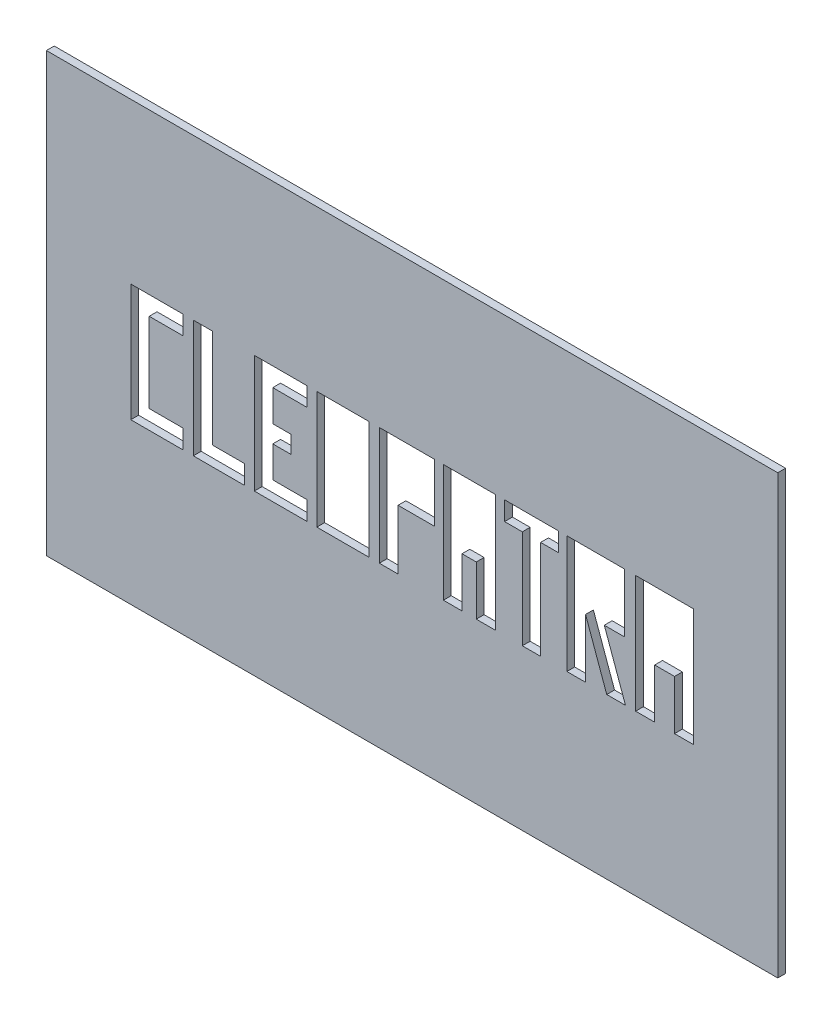
SolidWorks part; units mm, degrees
ref_plane "Front Plane" through (0, 0, 0) normal (0, 0, 1) x (1, 0, 0)
ref_plane "Top Plane" through (0, 0, 0) normal (0, 1, 0) x (1, 0, 0)
ref_plane "Right Plane" through (0, 0, 0) normal (1, 0, 0) x (0, 0, -1)
sketch "Sketch1" plane through (0, 0, 0) normal (0, 0, 1) x (1, 0, 0)
  line L1 (-148.59, 88.9) -> (148.59, 88.9)
  line L2 (-148.59, 88.9) -> (-148.59, -88.9)
  line L3 (-148.59, -88.9) -> (148.59, -88.9)
  line L4 (148.59, 88.9) -> (148.59, -88.9)
  line L5 (-148.59, 88.9) -> (148.59, -88.9) construction
  line L6 (-148.59, -88.9) -> (148.59, 88.9) construction
  point P1 (0, 0)
  dimension "D1" = 297.18
  dimension "D2" = 177.8
extrude "Boss-Extrude1" add sketch "Sketch1" along normal blind 3.175
ref_plane "Plane1" through (0, 0, 3.175) normal (0, 0, 1) x (1, 0, 0)
sketch "Sketch3" plane through (0, 0, 3.175) normal (0, 0, 1) x (1, 0, 0)
  line L0 (-114.3, 0) -> (114.3, 0)
  line L1 (-114.3, 23.886) -> (114.3, 23.886)
  line L2 (-114.3, 23.886) -> (-114.3, -23.886)
  line L3 (-114.3, -23.886) -> (114.3, -23.886)
  line L4 (114.3, 23.886) -> (114.3, -23.886)
  line L5 (-114.3, 23.886) -> (114.3, -23.886) construction
  line L6 (-114.3, -23.886) -> (114.3, 23.886) construction
  line L7 (114.3, 0) -> (114.3, 23.886)
  line L8 (-114.3, 23.886) -> (-88.9, 23.886) construction
  line L9 (-88.9, 23.886) -> (-88.9, -23.886) construction
  line L10 (-88.9, -23.886) -> (-64.111, -23.886) construction
  line L11 (-64.111, -23.886) -> (-64.111, 23.886) construction
  line L12 (-64.111, 23.886) -> (-38.711, 23.886) construction
  line L13 (-38.711, 23.886) -> (-38.711, -23.886) construction
  line L14 (-38.711, -23.886) -> (-13.311, -23.886) construction
  line L15 (-38.711, -23.886) -> (-13.311, -23.886) construction
  line L16 (-13.311, -23.886) -> (-13.311, 23.886) construction
  line L17 (-13.311, 23.886) -> (12.7173, 23.886) construction
  line L18 (12.7173, 23.886) -> (12.7173, -23.886) construction
  line L19 (12.7173, -23.886) -> (37.5864, -23.886) construction
  line L20 (37.5864, -23.886) -> (37.5864, 23.886) construction
  line L21 (37.5864, 23.886) -> (62.8944, 23.886) construction
  line L22 (62.8944, 23.886) -> (62.8944, -23.886) construction
  line L23 (62.8944, -23.886) -> (90.8355, -23.886) construction
  line L24 (90.8355, -23.886) -> (90.8355, 23.886) construction
  line L25 (70.4868, 0) -> (78.1068, 0)
  line L26 (-114.3, 23.886) -> (-106.8152, 23.886)
  line L27 (-114.3, 23.886) -> (-114.3, -23.886)
  line L28 (-114.3, -23.886) -> (-106.8152, -23.886)
  line L29 (-106.8152, 23.886) -> (-106.8152, -23.886)
  line L30 (-88.9, 23.886) -> (-81.1854, 23.886)
  line L31 (-88.9, 23.886) -> (-88.9, -23.886)
  line L32 (-88.9, -23.886) -> (-81.1854, -23.886)
  line L33 (-81.1854, 23.886) -> (-81.1854, -23.886)
  line L34 (-64.111, 23.886) -> (-56.6089, 23.886)
  line L35 (-64.111, 23.886) -> (-64.111, -23.886)
  line L36 (-64.111, -23.886) -> (-56.6089, -23.886)
  line L37 (-56.6089, 23.886) -> (-56.6089, -23.886)
  line L38 (-64.111, -23.886) -> (-42.7407, -23.886)
  line L39 (-64.111, -23.886) -> (-64.111, -16.2136)
  line L40 (-64.111, -16.2136) -> (-42.7407, -16.2136)
  line L41 (-42.7407, -23.886) -> (-42.7407, -16.2136)
  line L42 (-64.111, 23.886) -> (-42.7407, 23.886)
  line L43 (-64.111, 23.886) -> (-64.111, 16.2625)
  line L44 (-64.111, 16.2625) -> (-42.7407, 16.2625)
  line L45 (-42.7407, 23.886) -> (-42.7407, 16.2625)
  line L46 (-64.1233, 3.5401) -> (-49.2238, 3.5401)
  line L47 (-64.1233, 3.5401) -> (-64.1233, -3.5401)
  line L48 (-64.1233, -3.5401) -> (-49.2238, -3.5401)
  line L49 (-49.2238, 3.5401) -> (-49.2238, -3.5401)
  line L50 (-64.1233, 3.5401) -> (-49.2238, -3.5401) construction
  line L51 (-64.1233, -3.5401) -> (-49.2238, 3.5401) construction
  line L52 (-88.9, -23.886) -> (-68.0194, -23.886)
  line L53 (-88.9, -23.886) -> (-88.9, -16.2136)
  line L54 (-88.9, -16.2136) -> (-68.0194, -16.2136)
  line L55 (-68.0194, -23.886) -> (-68.0194, -16.2136)
  line L56 (-38.711, 23.886) -> (-17.462, 23.886)
  line L57 (-38.711, 23.886) -> (-38.711, -23.886)
  line L58 (-38.711, -23.886) -> (-17.462, -23.886)
  line L59 (-17.462, 23.886) -> (-17.462, -23.886)
  line L60 (-31.1625, 16.2136) -> (-25.0105, 16.2136)
  line L61 (-31.1625, 16.2136) -> (-31.1625, -16.2136)
  line L62 (-31.1625, -16.2136) -> (-25.0105, -16.2136)
  line L63 (-25.0105, 16.2136) -> (-25.0105, -16.2136)
  line L64 (-31.1625, 16.2136) -> (-25.0105, -16.2136) construction
  line L65 (-31.1625, -16.2136) -> (-25.0105, 16.2136) construction
  line L66 (-114.3, 23.886) -> (-93.1225, 23.886)
  line L67 (-114.3, 23.886) -> (-114.3, 16.2625)
  line L68 (-114.3, 16.2625) -> (-93.1225, 16.2625)
  line L69 (-93.1225, 23.886) -> (-93.1225, 16.2625)
  line L70 (-114.3, -23.886) -> (-93.1225, -23.886)
  line L71 (-114.3, -23.886) -> (-114.3, -16.2136)
  line L72 (-114.3, -16.2136) -> (-93.1225, -16.2136)
  line L73 (-93.1225, -23.886) -> (-93.1225, -16.2136)
  line L74 (-13.311, 23.886) -> (-5.7004, 23.886)
  line L75 (-13.311, 23.886) -> (-13.311, -23.886)
  line L76 (-13.311, -23.886) -> (-5.7004, -23.886)
  line L77 (-5.7004, 23.886) -> (-5.7004, -23.886)
  line L78 (-13.311, 23.886) -> (9.0455, 23.886)
  line L79 (-13.311, 23.886) -> (-13.311, 16.2136)
  line L80 (-13.311, 16.2136) -> (9.0455, 16.2136)
  line L81 (9.0455, 23.886) -> (9.0455, 16.2136)
  line L82 (9.0455, 23.886) -> (1.4995, 23.886)
  line L83 (9.0455, 23.886) -> (9.0455, 0.3134)
  line L84 (9.0455, 0.3134) -> (1.4995, 0.3134)
  line L85 (1.4995, 23.886) -> (1.4995, 0.3134)
  line L86 (9.0455, 0.3134) -> (-13.311, 0.3134)
  line L87 (9.0455, 0.3134) -> (9.0455, 7.8363)
  line L88 (9.0455, 7.8363) -> (-13.311, 7.8363)
  line L89 (-13.311, 0.3134) -> (-13.311, 7.8363)
  line L90 (12.7173, 23.886) -> (20.2805, 23.886)
  line L91 (12.7173, 23.886) -> (12.7173, -23.886)
  line L92 (12.7173, -23.886) -> (20.2805, -23.886)
  line L93 (20.2805, 23.886) -> (20.2805, -23.886)
  line L94 (12.7173, 23.886) -> (33.7975, 23.886)
  line L95 (12.7173, 23.886) -> (12.7173, 16.2136)
  line L96 (12.7173, 16.2136) -> (33.7975, 16.2136)
  line L97 (33.7975, 23.886) -> (33.7975, 16.2136)
  line L98 (33.7975, 23.886) -> (26.0735, 23.886)
  line L99 (33.7975, 23.886) -> (33.7975, -23.886)
  line L100 (33.7975, -23.886) -> (26.0735, -23.886)
  line L101 (26.0735, 23.886) -> (26.0735, -23.886)
  line L102 (12.7173, 4.0748) -> (33.7975, 4.0748)
  line L103 (12.7173, 4.0748) -> (12.7173, -3.7498)
  line L104 (12.7173, -3.7498) -> (33.7975, -3.7498)
  line L105 (33.7975, 4.0748) -> (33.7975, -3.7498)
  line L106 (37.5864, 23.886) -> (59.4273, 23.886)
  line L107 (37.5864, 23.886) -> (37.5864, 16.2136)
  line L108 (37.5864, 16.2136) -> (59.4273, 16.2136)
  line L109 (59.4273, 23.886) -> (59.4273, 16.2136)
  line L110 (44.7838, 23.886) -> (52.2299, 23.886)
  line L111 (44.7838, 23.886) -> (44.7838, -23.886)
  line L112 (44.7838, -23.886) -> (52.2299, -23.886)
  line L113 (52.2299, 23.886) -> (52.2299, -23.886)
  line L114 (44.7838, 23.886) -> (52.2299, -23.886) construction
  line L115 (44.7838, -23.886) -> (52.2299, 23.886) construction
  line L116 (62.8944, 23.886) -> (70.4868, 23.886)
  line L117 (62.8944, 23.886) -> (62.8944, -23.886)
  line L118 (62.8944, -23.886) -> (70.4868, -23.886)
  line L119 (70.4868, 23.886) -> (70.4868, -23.886)
  line L120 (62.8944, 23.886) -> (86.2859, 23.886)
  line L121 (62.8944, 23.886) -> (62.8944, 16.2136)
  line L122 (62.8944, 16.2136) -> (86.2859, 16.2136)
  line L123 (86.2859, 23.886) -> (86.2859, 16.2136)
  line L124 (86.2859, 23.886) -> (78.913, 23.886)
  line L125 (86.2859, 23.886) -> (86.2859, 7.8363)
  line L126 (86.2859, 7.8363) -> (78.913, 7.8363)
  line L127 (78.913, 23.886) -> (78.913, 7.8363)
  line L128 (86.2859, 7.8363) -> (62.8944, 7.8363)
  line L129 (86.2859, 7.8363) -> (86.2859, 0)
  line L130 (86.2859, 0) -> (62.8944, 0)
  line L131 (62.8944, 7.8363) -> (62.8944, 0)
  line L132 (70.4868, 0) -> (79.0885, -23.886)
  line L133 (78.1068, 0) -> (86.7085, -23.886)
  line L134 (79.0885, -23.886) -> (86.7085, -23.886)
  line L135 (-93.1225, 23.886) -> (-114.3, 23.886)
  line L136 (90.8355, 23.886) -> (98.5742, 23.886)
  line L137 (90.8355, 23.886) -> (90.8355, -23.886)
  line L138 (90.8355, -23.886) -> (98.5742, -23.886)
  line L139 (98.5742, 23.886) -> (98.5742, -23.886)
  line L140 (90.8355, 23.886) -> (114.3, 23.886)
  line L141 (90.8355, 23.886) -> (90.8355, 16.2136)
  line L142 (90.8355, 16.2136) -> (114.3, 16.2136)
  line L143 (114.3, 23.886) -> (114.3, 16.2136)
  line L144 (114.3, 23.886) -> (106.6318, 23.886)
  line L145 (114.3, 23.886) -> (114.3, -23.886)
  line L146 (114.3, -23.886) -> (106.6318, -23.886)
  line L147 (106.6318, 23.886) -> (106.6318, -23.886)
  line L148 (90.8355, 4.0748) -> (114.3, 4.0748)
  line L149 (90.8355, 4.0748) -> (90.8355, -3.7498)
  line L150 (90.8355, -3.7498) -> (114.3, -3.7498)
  line L151 (114.3, 4.0748) -> (114.3, -3.7498)
  line L152 (-114.3, -23.886) -> (-93.1225, -23.886)
  line L153 (-93.1225, -16.2136) -> (-106.8152, -16.2136)
  line L154 (-106.8152, -16.2136) -> (-106.8152, 16.2625)
  line L155 (-106.8152, 16.2625) -> (-93.1225, 16.2625)
  point P0 (0, 0)
  point P36 (-56.6736, 0)
  point P46 (-28.0865, 0)
  point P83 (48.5069, 0)
  dimension "D1" = 228.6
  dimension "D2" = 7.62
extrude "Cut-Extrude4" cut sketch "Sketch3" against normal blind 3.175 contours L69 L1 L29 L68 | L2 L68 L29 L1 | L68 L27 L0 L29 | L2 L72 L29 L0 | L72 L27 L3 L29 | L3 L73 L72 L29 | L33 L1 L31 L0 | L31 L54 L33 L0 | L3 L55 L54 L33 | L54 L31 L3 L33 | L46 L35 L0 L37 | L49 L46 L37 L0 | L49 L0 L37 L48 | L35 L48 L37 L0 | L48 L35 L40 L37 | L40 L35 L3 L37 | L3 L41 L40 L37 | L35 L46 L37 L44 | L35 L44 L37 L1 | L45 L1 L37 L44 | L60 L63 L0 L59 L1 L57 L61 | L0 L63 L62 L61 L57 L3 L59 | L77 L0 L75 L3 | L75 L80 L77 L1 | L88 L77 L80 L75 | L77 L88 L75 L86 | L85 L88 L77 L86 | L83 L88 L85 L84 | L88 L83 L80 L85 | L78 L85 L80 L81 | L85 L1 L77 L80 | L77 L86 L75 L0 | L63 L60 L61 L0 | L63 L0 L61 L62 | L88 L85 L80 L77 | L91 L96 L93 L1 | L101 L1 L93 L96 | L94 L101 L96 L97 | L101 L102 L99 L96 | L91 L102 L93 L96 | L104 L91 L3 L93 | L104 L101 L3 L99 | L102 L93 L0 L101 | L93 L104 L101 L0 | L91 L104 L93 L0 | L102 L91 L0 L93 | L102 L101 L0 L99 | L101 L104 L99 L0 | L93 L102 L101 L96 | L111 L1 L107 L108 | L113 L106 L111 L108 | L1 L113 L108 L109 | L113 L108 L111 L0 | L117 L122 L119 L1 | L127 L1 L119 L122 | L113 L0 L111 L3 | L120 L127 L122 L123 | L128 L127 L122 L119 | L128 L119 L122 L117 | L122 L127 L126 L125 | L129 L126 L128 L119 L0 | L133 L0 L132 L3 | L119 L0 L117 L3 | L119 L128 L117 L0 | L137 L142 L139 L1 | L147 L1 L139 L142 | L137 L148 L139 L142 | L140 L147 L142 L4 | L147 L148 L7 L142 | L150 L147 L3 L145 | L139 L148 L147 L142 | L137 L150 L139 L0 | L148 L137 L0 L139 | L148 L147 L0 L145 | L139 L150 L147 L0 | L150 L137 L3 L139 | L148 L139 L0 L147 | L147 L150 L4 L0
